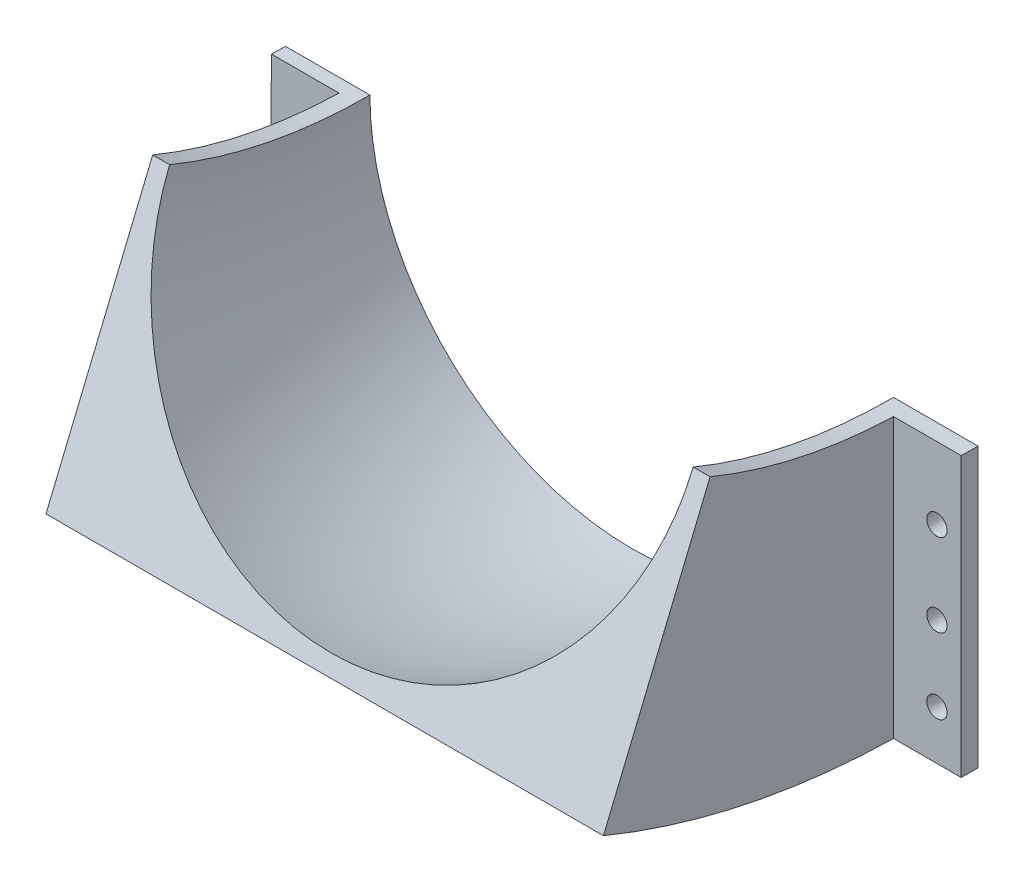
SolidWorks part; units mm, degrees
ref_plane "Front Plane" through (0, 0, 0) normal (0, 0, 1) x (1, 0, 0)
ref_plane "Top Plane" through (0, 0, 0) normal (0, 1, 0) x (1, 0, 0)
ref_plane "Right Plane" through (0, 0, 0) normal (1, 0, 0) x (0, 0, -1)
sketch "Sketch9" plane through (0, 0, 0) normal (0, 0, 1) x (1, 0, 0)
  line L0 (-49.2252, -98.425) -> (-52.4002, -98.425)
  line L1 (-52.4002, -115.251) -> (-52.4002, -77.9954) construction
  line L2 (-65.1002, -98.425) -> (-52.4002, -98.425) construction
  line L3 (49.2252, -98.425) -> (52.4002, -98.425)
  line L4 (52.4002, -98.425) -> (52.4002, -150.8252)
  line L5 (-52.4002, -98.425) -> (-52.4002, -150.8252)
  line L6 (-52.4002, -150.8252) -> (52.4002, -150.8252)
  arc A0 (-49.2252, -98.425) -> (49.2252, -98.425) centre (0, -98.425) ccw construction
  arc A1 (-49.2252, -98.425) -> (49.2252, -98.425) centre (0, -98.425) ccw
ref_axis "Axis2" through (-38.0489, 0, 0) along (1, 0, 0)
revolve "Revolve8" add sketch "Sketch9" angle 22.5 about axis through (-38.0489, 0, 0) along (1, 0, 0)
sketch "Sketch10" plane through (52.4002, 0, 0) normal (1, 0, 0) x (0, 0, -1)
  line L0 (0, -98.425) -> (0, -150.8252)
  line L1 (0, -150.8252) -> (-3.1748, -150.7918)
  line L2 (-3.1748, -150.7918) -> (-3.1748, -98.3738)
  arc A0 (-57.7183, -139.3443) -> (0, -150.8252) centre (0, 0) ccw construction
  arc A1 (-37.6656, -90.9328) -> (0, -98.425) centre (0, 0) ccw construction
  arc A2 (-3.1748, -98.3738) -> (0, -98.425) centre (0, 0) ccw
  dimension "D1" = 3.175
sketch "Sketch11" plane through (-52.4002, 0, 0) normal (-1, 0, 0) x (0, 0, 1)
  line L0 (0, -98.425) -> (0, -150.8252)
  line L2 (3.1748, -150.7918) -> (2.6232, -98.39)
  arc A0 (0, -150.8252) -> (57.7183, -139.3443) centre (0, 0) ccw construction
  arc A2 (0, -98.425) -> (37.6656, -90.9328) centre (0, 0) ccw construction
  arc A3 (0, -98.425) -> (2.6232, -98.39) centre (0, 0) ccw
  arc A4 (0, -150.8252) -> (3.1748, -150.7918) centre (0, 0) ccw
  dimension "D1" = 3.175
extrude "Boss-Extrude3" add sketch "Sketch11" along normal blind 12.7
extrude "Boss-Extrude4" add sketch "Sketch10" along normal blind 12.7
sketch "Sketch12" plane through (0, 0, 3.1748) normal (0, 0, 1) x (1, 0, 0)
  circle A1 centre (60.5502, -111.886) radius 1.905
  circle A2 centre (60.5502, -111.886) radius 1.905
  circle A3 centre (60.5502, -141.5668) radius 1.905
  circle A4 centre (60.5502, -141.5668) radius 1.905
  circle A5 centre (60.5502, -127.4445) radius 1.905
  circle A6 centre (60.5502, -127.4445) radius 1.905
  dimension "D1" = 0
  dimension "D2" = 0
  dimension "D3" = 0
extrude "Cut-Extrude4" cut sketch "Sketch12" against normal blind 3.175
sketch "Sketch13" plane through (0, -0.0084, 1.5877) normal (0, 0.0105, 0.9999) x (1, 0, 0)
  circle A1 centre (-60.754, -141.5219) radius 1.905
  circle A2 centre (-60.754, -141.5219) radius 1.905
  circle A3 centre (-60.754, -112.4795) radius 1.905
  circle A4 centre (-60.754, -112.4795) radius 1.905
  circle A5 centre (-60.754, -127.4445) radius 1.905
  circle A6 centre (-60.754, -127.4445) radius 1.905
  dimension "D1" = 0
  dimension "D2" = 0
  dimension "D3" = 0
extrude "Cut-Extrude5" cut sketch "Sketch13" against normal blind 3.175
